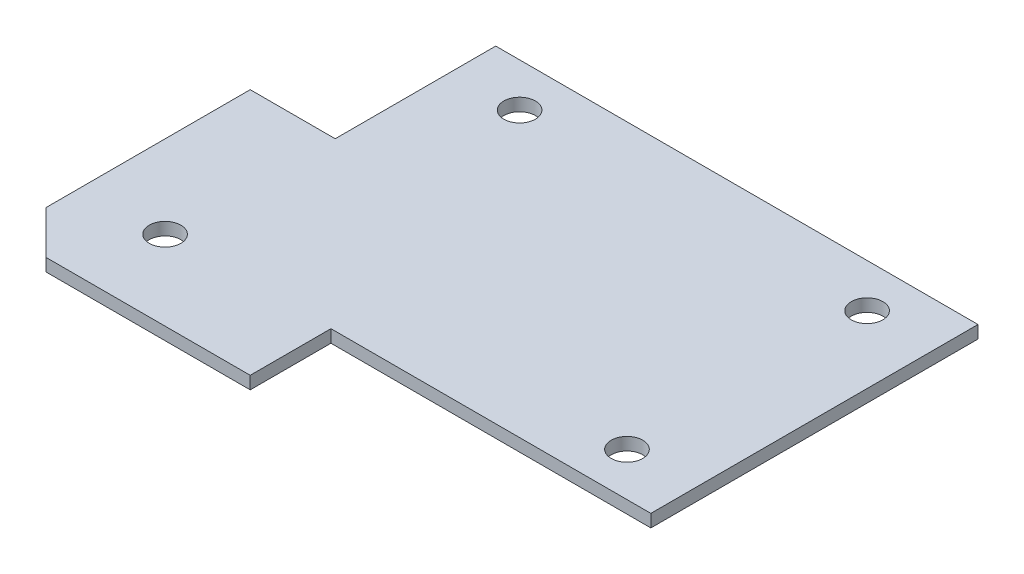
SolidWorks part; units mm, degrees
ref_plane "Front Plane" through (0, 0, 0) normal (0, 0, 1) x (1, 0, 0)
ref_plane "Top Plane" through (0, 0, 0) normal (0, 1, 0) x (1, 0, 0)
ref_plane "Right Plane" through (0, 0, 0) normal (1, 0, 0) x (0, 0, -1)
sketch "Sketch1" plane through (0, 0, 0) normal (0, 1, 0) x (1, 0, 0)
  line L1 (-1.7825, -28.3447) -> (33.8509, -28.3447)
  line L2 (-31.4806, 2.0264) -> (-31.4806, 27.4359)
  line L3 (-31.4806, 27.4359) -> (33.8509, 27.4359)
  line L4 (33.8509, -28.3447) -> (33.8509, 27.4359)
  line L7 (-44.9335, -41.1246) -> (-1.7825, -41.1246)
  line L8 (-44.9335, -41.1246) -> (-44.9335, 2.0264)
  line L9 (-44.9335, 2.0264) -> (-31.4806, 2.0264)
  line L10 (-1.7825, -41.1246) -> (-1.7825, -28.3447)
  point P0 (0, 0)
extrude "Boss-Extrude1" add sketch "Sketch1" along normal blind 2
sketch "Sketch2" plane through (0, 2, 0) normal (0, 1, 0) x (1, 0, 0)
  line L0 (-20.026, -21.3446) -> (-55.2841, -20.4558)
  line L1 (-55.2841, -20.4558) -> (-55.2841, -41.0477)
  line L2 (-55.2841, -41.0477) -> (-20.026, -21.3446)
chamfer "Chamfer1" distance 8 angle 45 1 edges at (-44.9335, 1, 41.1246)
sketch "Sketch3" plane through (0, 2, 0) normal (0, 1, 0) x (1, 0, 0)
  line L0 (-29.4806, 25.4359) -> (31.8509, 25.4359)
  line L1 (31.8509, 25.4359) -> (31.8509, -26.3447)
  line L2 (31.8509, -26.3447) -> (-3.7825, -26.3447)
  line L3 (-3.7825, -26.3447) -> (-3.7825, -39.1246)
  line L4 (-3.7825, -39.1246) -> (-36.1051, -39.1246)
  line L5 (-36.1051, -39.1246) -> (-42.9335, -32.2962)
  line L6 (-42.9335, -32.2962) -> (-42.9335, 0.0264)
  line L7 (-42.9335, 0.0264) -> (-29.4806, 0.0264)
  line L8 (-29.4806, 0.0264) -> (-29.4806, 25.4359)
  line L9 (-31.4806, 2.0264) -> (-44.9335, 2.0264) construction
  line L10 (-44.9335, 2.0264) -> (-44.9335, -33.1246) construction
  line L11 (-44.9335, -33.1246) -> (-36.9335, -41.1246) construction
  line L12 (-36.9335, -41.1246) -> (-1.7825, -41.1246) construction
  line L13 (-1.7825, -41.1246) -> (-1.7825, -28.3447) construction
  line L14 (-1.7825, -28.3447) -> (33.8509, -28.3447) construction
  line L15 (33.8509, -28.3447) -> (33.8509, 27.4359) construction
  line L16 (-31.4806, 27.4359) -> (-31.4806, 2.0264) construction
  line L17 (33.8509, 27.4359) -> (-31.4806, 27.4359) construction
  dimension "D1" = 2
  dimension "D2" = 2
  dimension "D3" = 2
  dimension "D4" = 2
  dimension "D5" = 2
  dimension "D6" = 2
  dimension "D7" = 2
  dimension "D8" = 2
  dimension "D9" = 2
extrude "Boss-Extrude2" add sketch "Sketch3" along normal blind 2
sketch "Sketch4" plane through (0, 0, 0) normal (0, -1, 0) x (1, 0, 0)
  line L1 (49.8844, -45.7944) -> (-49.8844, -45.7944)
  line L2 (49.8844, -45.7944) -> (49.8844, 45.7944)
  line L3 (49.8844, 45.7944) -> (-49.8844, 45.7944)
  line L4 (-49.8844, -45.7944) -> (-49.8844, 45.7944)
  line L5 (49.8844, -45.7944) -> (-49.8844, 45.7944) construction
  line L6 (49.8844, 45.7944) -> (-49.8844, -45.7944) construction
  point P0 (0, 0)
extrude "Cut-Extrude1" cut sketch "Sketch4" against normal blind 2
sketch "Sketch5" plane through (0, 4, 0) normal (0, 1, 0) x (1, 0, 0)
  line L0 (1.1852, 18.5456) -> (1.1852, -0.4544) construction
  line L5 (-3.7825, -26.3447) -> (31.8509, -26.3447) construction
  line L6 (31.8509, -0.4544) -> (-18.8148, -0.4544) construction
  line L7 (31.8509, -26.3447) -> (31.8509, 25.4359) construction
  line L8 (31.8509, 25.4359) -> (-29.4806, 25.4359) construction
  line L9 (-42.9335, 0.0264) -> (-42.9335, -32.2962) construction
  line L10 (21.1852, -0.4544) -> (21.1852, 18.5456) construction
  line L11 (21.1852, -19.4544) -> (1.1852, -19.4544) construction
  line L12 (21.1852, -19.4544) -> (21.1852, -0.4544) construction
  line L13 (1.1852, 18.5456) -> (-18.8148, 18.5456) construction
  line L14 (-18.8148, -19.4544) -> (-18.8148, -0.4544) construction
  line L15 (21.1852, -19.4544) -> (1.1852, -0.4544) construction
  line L16 (1.1852, -0.4544) -> (-18.8148, -19.4544) construction
  line L17 (21.1852, 18.5456) -> (1.1852, -0.4544) construction
  line L18 (21.1852, 18.5456) -> (1.1852, 18.5456) construction
  line L19 (1.1852, 25.4359) -> (1.1852, 18.5456) construction
  line L20 (1.1852, -0.4544) -> (-18.8148, 18.5456) construction
  line L21 (-18.8148, -0.4544) -> (-18.8148, 18.5456) construction
  line L22 (-18.8148, -0.4544) -> (-42.9335, -0.4544) construction
  line L23 (1.1852, -19.4544) -> (-18.8148, -19.4544) construction
  line L24 (1.1852, -0.4544) -> (1.1852, -19.4544) construction
  line L25 (1.1852, -19.4544) -> (1.1852, -26.3447) construction
  line L26 (-39.5193, -35.7104) -> (-18.8148, -16.0411) construction
  line L27 (-23.2619, -30.4944) -> (-25.7619, -30.4944) construction
  line L28 (-42.9335, -32.2962) -> (-36.1051, -39.1246) construction
  line L29 (-29.8548, -26.5291) -> (-29.8548, -16.0411) construction
  line L30 (-29.8548, -16.0411) -> (-18.8148, -16.0411) construction
  circle A0 centre (-18.8148, 18.5456) radius 2.5
  circle A1 centre (21.1852, 18.5456) radius 2.5
  circle A2 centre (21.1852, -19.4544) radius 2.5
  circle A4 centre (-29.8548, -26.5291) radius 2.5
  point P0 (0, 0)
  point P14 (1.1852, -0.4544)
  dimension "D3" = 5
  dimension "D4" = 11.04
  dimension "D1" = 40
  dimension "D2" = 38
extrude "Cut-Extrude2" cut sketch "Sketch5" against normal blind 2
sketch "Sketch6" plane through (0, 4, 0) normal (0, 1, 0) x (1, 0, 0)
  line L0 (31.8509, 25.4359) -> (46.8509, 25.4359)
  line L1 (46.8509, 25.4359) -> (46.8509, -26.3447)
  line L2 (46.8509, -26.3447) -> (31.8509, -26.3447)
  line L3 (31.8509, 25.4359) -> (31.8509, -26.3447)
  dimension "D1" = 15
extrude "Boss-Extrude3" add sketch "Sketch6" against normal up to surface (2 mm away) up to face at (-29.8548, 2, 29.0291)
sketch "Sketch7" plane through (0, 4, 0) normal (0, 1, 0) x (1, 0, 0)
  line L0 (21.1852, 18.5456) -> (36.1852, 18.5456) construction
  line L1 (36.1852, 18.5456) -> (36.1852, -19.4544) construction
  line L2 (21.1852, -19.4544) -> (36.1852, -19.4544) construction
  circle A0 centre (36.1852, 18.5456) radius 2.5
  circle A1 centre (36.1852, -19.4544) radius 2.5
  circle A2 centre (-18.8148, 18.5456) radius 2.5 construction
  dimension "D1" = 15
extrude "Cut-Extrude3" cut sketch "Sketch7" against normal through all
sketch "Sketch8" plane through (0, 4, 0) normal (0, 1, 0) x (1, 0, 0)
  circle A0 centre (21.1852, 18.5456) radius 3.6303
  circle A1 centre (21.1852, -19.4544) radius 3.8129
extrude "Boss-Extrude4" add sketch "Sketch8" against normal up to surface (2 mm away) up to face at (36.1852, 2, -16.0456)
